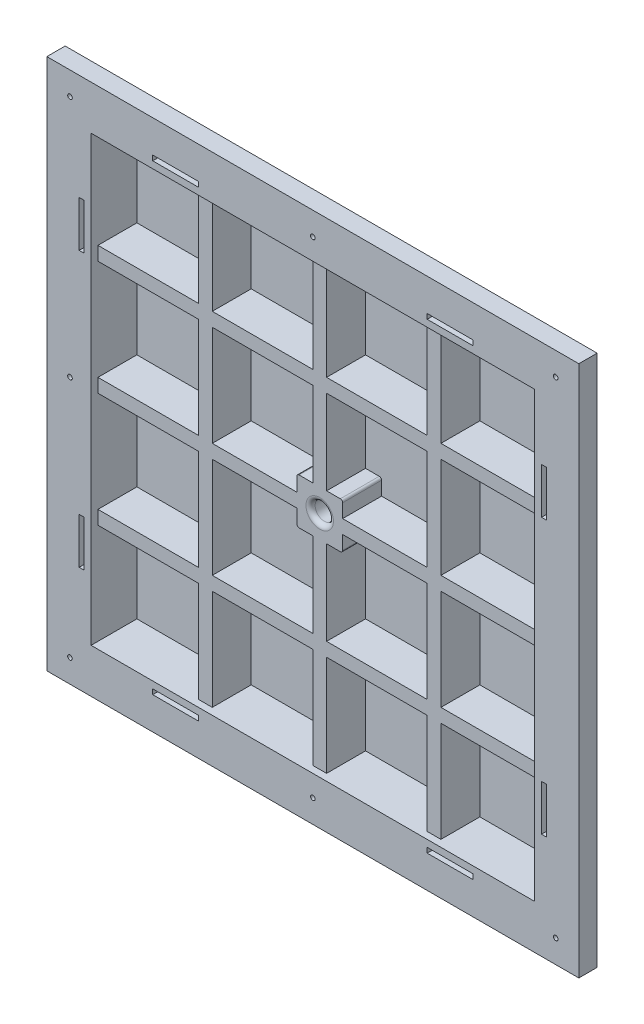
SolidWorks part; units mm, degrees
ref_plane "Front Plane" through (0, 0, 0) normal (0, 0, 1) x (1, 0, 0)
ref_plane "Top Plane" through (0, 0, 0) normal (0, 1, 0) x (1, 0, 0)
ref_plane "Right Plane" through (0, 0, 0) normal (1, 0, 0) x (0, 0, -1)
sketch "Sketch1" plane through (0, 0, 1355.7244) normal (0, 0, 1) x (1, 0, 0)
  line L22 (813.5427, 831.1782) -> (813.5427, 1030.7782)
  line L23 (613.9427, 831.1782) -> (813.5427, 831.1782)
  line L24 (613.9427, 1030.7782) -> (613.9427, 831.1782)
  line L25 (813.5427, 1030.7782) -> (613.9427, 1030.7782)
  line L26 (813.5427, 831.1782) -> (813.5427, 1030.7782)
  line L27 (613.9427, 831.1782) -> (813.5427, 831.1782)
  line L28 (613.9427, 1030.7782) -> (613.9427, 831.1782)
  line L29 (813.5427, 1030.7782) -> (613.9427, 1030.7782)
  dimension "D1" = 2.2
extrude "Boss-Extrude1" add sketch "Sketch1" against normal blind 20
sketch "Sketch2" plane through (0, 0, 1355.7244) normal (0, 0, 1) x (1, 0, 0)
  line L0 (826.8427, 1044.0782) -> (600.6427, 1044.0782)
  line L1 (600.6427, 1044.0782) -> (600.6427, 817.8782)
  line L2 (600.6427, 817.8782) -> (826.8427, 817.8782)
  line L3 (826.8427, 817.8782) -> (826.8427, 1044.0782)
  line L8 (823.8427, 820.8782) -> (823.8427, 1041.0782)
  line L9 (823.8427, 1041.0782) -> (603.6427, 1041.0782)
  line L10 (603.6427, 1041.0782) -> (603.6427, 820.8782)
  line L11 (603.6427, 820.8782) -> (823.8427, 820.8782)
  line L12 (823.8427, 820.8782) -> (823.8427, 1041.0782)
  line L13 (823.8427, 1041.0782) -> (603.6427, 1041.0782)
  line L14 (603.6427, 1041.0782) -> (603.6427, 820.8782)
  line L15 (603.6427, 820.8782) -> (823.8427, 820.8782)
  dimension "D1" = 0.1
  dimension "D2" = 3
extrude "Boss-Extrude2" add sketch "Sketch2" against normal blind 5 separate body
sketch "Sketch3" plane through (0, 0, 1355.7244) normal (0, 0, 1) x (1, 0, 0)
  line L4 (616.9427, 930.9782) -> (810.5427, 930.9782) construction
  line L5 (616.9427, 927.9782) -> (660.8427, 927.9782)
  line L6 (616.9427, 933.9782) -> (660.8427, 933.9782)
  line L7 (713.7427, 1027.7782) -> (713.7427, 834.1782) construction
  line L8 (616.9427, 834.1782) -> (810.5427, 834.1782)
  line L9 (810.5427, 834.1782) -> (810.5427, 1027.7782)
  line L10 (810.5427, 1027.7782) -> (616.9427, 1027.7782)
  line L11 (616.9427, 1027.7782) -> (616.9427, 834.1782)
  line L12 (616.9427, 834.1782) -> (660.8427, 834.1782)
  line L13 (810.5427, 834.1782) -> (810.5427, 878.0782)
  line L14 (810.5427, 1027.7782) -> (766.6427, 1027.7782)
  line L15 (616.9427, 1027.7782) -> (616.9427, 983.8782)
  line L16 (710.7427, 1027.7782) -> (710.7427, 983.8782)
  line L17 (716.7427, 1027.7782) -> (716.7427, 983.8782)
  line L18 (716.7427, 933.9782) -> (760.6427, 933.9782)
  line L19 (616.9427, 933.9782) -> (810.5427, 933.9782) construction
  line L20 (710.7427, 927.9782) -> (710.7427, 884.0782)
  line L21 (710.7427, 1027.7782) -> (710.7427, 834.1782) construction
  line L22 (716.7427, 927.9782) -> (716.7427, 884.0782)
  line L23 (716.7427, 1027.7782) -> (716.7427, 834.1782) construction
  line L24 (716.7427, 927.9782) -> (760.6427, 927.9782)
  line L25 (616.9427, 927.9782) -> (810.5427, 927.9782) construction
  line L26 (663.8427, 933.9782) -> (663.8427, 1027.7782) construction
  line L27 (710.7427, 980.8782) -> (616.9427, 980.8782) construction
  line L28 (666.8427, 933.9782) -> (666.8427, 977.8782)
  line L29 (660.8427, 933.9782) -> (660.8427, 977.8782)
  line L30 (710.7427, 983.8782) -> (666.8427, 983.8782)
  line L31 (710.7427, 977.8782) -> (666.8427, 977.8782)
  line L32 (660.8427, 983.8782) -> (616.9427, 983.8782)
  line L33 (710.7427, 983.8782) -> (616.9427, 983.8782) construction
  line L34 (660.8427, 983.8782) -> (660.8427, 1027.7782)
  line L35 (660.8427, 933.9782) -> (660.8427, 1027.7782) construction
  line L36 (666.8427, 983.8782) -> (666.8427, 1027.7782)
  line L37 (666.8427, 933.9782) -> (666.8427, 1027.7782) construction
  line L38 (660.8427, 977.8782) -> (616.9427, 977.8782)
  line L39 (710.7427, 977.8782) -> (616.9427, 977.8782) construction
  line L40 (760.6427, 933.9782) -> (760.6427, 977.8782)
  line L41 (766.6427, 933.9782) -> (766.6427, 977.8782)
  line L42 (766.6427, 977.8782) -> (810.5427, 977.8782)
  line L43 (766.6427, 983.8782) -> (810.5427, 983.8782)
  line L44 (716.7427, 983.8782) -> (760.6427, 983.8782)
  line L45 (716.7427, 977.8782) -> (760.6427, 977.8782)
  line L46 (760.6427, 983.8782) -> (760.6427, 1027.7782)
  line L47 (766.6427, 983.8782) -> (766.6427, 1027.7782)
  line L48 (710.7427, 881.0782) -> (616.9427, 881.0782) construction
  line L49 (663.8427, 927.9782) -> (663.8427, 834.1782) construction
  line L50 (766.6427, 878.0782) -> (766.6427, 834.1782)
  line L51 (760.6427, 878.0782) -> (760.6427, 834.1782)
  line L52 (716.7427, 884.0782) -> (760.6427, 884.0782)
  line L53 (716.7427, 878.0782) -> (760.6427, 878.0782)
  line L54 (766.6427, 878.0782) -> (810.5427, 878.0782)
  line L55 (766.6427, 884.0782) -> (810.5427, 884.0782)
  line L56 (766.6427, 927.9782) -> (766.6427, 884.0782)
  line L57 (760.6427, 927.9782) -> (760.6427, 884.0782)
  line L58 (660.8427, 884.0782) -> (616.9427, 884.0782)
  line L59 (666.8427, 878.0782) -> (666.8427, 834.1782)
  line L60 (660.8427, 878.0782) -> (660.8427, 834.1782)
  line L61 (660.8427, 878.0782) -> (616.9427, 878.0782)
  line L62 (710.7427, 884.0782) -> (666.8427, 884.0782)
  line L63 (710.7427, 878.0782) -> (666.8427, 878.0782)
  line L64 (660.8427, 927.9782) -> (660.8427, 884.0782)
  line L65 (666.8427, 927.9782) -> (666.8427, 884.0782)
  line L66 (760.6427, 1027.7782) -> (716.7427, 1027.7782)
  line L67 (810.5427, 983.8782) -> (810.5427, 1027.7782)
  line L68 (710.7427, 1027.7782) -> (666.8427, 1027.7782)
  line L69 (660.8427, 1027.7782) -> (616.9427, 1027.7782)
  line L70 (616.9427, 977.8782) -> (616.9427, 933.9782)
  line L71 (710.7427, 977.8782) -> (710.7427, 933.9782)
  line L72 (716.7427, 977.8782) -> (716.7427, 933.9782)
  line L73 (810.5427, 933.9782) -> (810.5427, 977.8782)
  line L74 (666.8427, 933.9782) -> (710.7427, 933.9782)
  line L75 (666.8427, 927.9782) -> (710.7427, 927.9782)
  line L76 (616.9427, 927.9782) -> (616.9427, 884.0782)
  line L77 (616.9427, 878.0782) -> (616.9427, 834.1782)
  line L78 (666.8427, 834.1782) -> (710.7427, 834.1782)
  line L79 (716.7427, 834.1782) -> (760.6427, 834.1782)
  line L80 (710.7427, 878.0782) -> (710.7427, 834.1782)
  line L81 (716.7427, 878.0782) -> (716.7427, 834.1782)
  line L82 (810.5427, 884.0782) -> (810.5427, 927.9782)
  line L83 (766.6427, 834.1782) -> (810.5427, 834.1782)
  line L84 (766.6427, 927.9782) -> (810.5427, 927.9782)
  line L85 (766.6427, 933.9782) -> (810.5427, 933.9782)
  dimension "D1" = 3
  dimension "D2" = 3
  dimension "D3" = 3
  dimension "D4" = 3
  dimension "D5" = 3
  dimension "D6" = 3
  dimension "D7" = 3
  dimension "D8" = 3
  dimension "D9" = 3
extrude "Cut-Extrude2" cut sketch "Sketch3" against normal offset from surface (17 mm away) 3 up to face at (713.7427, 930.9782, 1335.7244)
sketch "Sketch4" plane through (0, 0, 1355.7244) normal (0, 0, 1) x (1, 0, 0)
  line L1 (600.6427, 1044.0782) -> (826.8427, 1044.0782)
  line L2 (600.6427, 1044.0782) -> (600.6427, 817.8782)
  line L3 (600.6427, 817.8782) -> (826.8427, 817.8782)
  line L4 (826.8427, 1044.0782) -> (826.8427, 817.8782)
  line L5 (810.5427, 834.1782) -> (616.9427, 834.1782)
  line L6 (810.5427, 834.1782) -> (810.5427, 1027.7782)
  line L7 (810.5427, 1027.7782) -> (616.9427, 1027.7782)
  line L8 (616.9427, 834.1782) -> (616.9427, 1027.7782)
  circle A0 centre (607.7427, 1036.9782) radius 1
  circle A1 centre (713.7427, 1036.9782) radius 1
  circle A2 centre (819.7427, 1036.9782) radius 1
  circle A3 centre (607.7427, 930.9782) radius 1
  circle A4 centre (607.7427, 824.9782) radius 1
  circle A5 centre (713.7427, 824.9782) radius 1
  circle A6 centre (819.7427, 824.9782) radius 1
extrude "Boss-Extrude3" add sketch "Sketch4" along normal blind 3
sketch "Sketch5" plane through (0, 0, 1355.7244) normal (0, 0, -1) x (-1, 0, 0)
  line L0 (-813.5427, 1030.7782) -> (-713.7427, 1030.7782) construction
  line L1 (-813.5427, 1030.7782) -> (-613.9427, 1030.7782) construction
  line L2 (-763.6427, 1030.7782) -> (-783.6427, 1030.7782)
  line L3 (-783.6427, 1030.7782) -> (-783.6427, 1032.9782)
  line L4 (-815.7427, 1032.9782) -> (-611.7427, 1032.9782) construction
  line L5 (-783.6427, 1032.9782) -> (-763.6427, 1032.9782)
  line L6 (-763.6427, 1032.9782) -> (-763.6427, 1030.7782)
  line L7 (-713.7427, 1030.7782) -> (-713.7427, 831.1782) construction
  line L8 (-613.9427, 831.1782) -> (-813.5427, 831.1782) construction
  line L9 (-613.9427, 930.9782) -> (-813.5427, 930.9782) construction
  line L10 (-613.9427, 1030.7782) -> (-613.9427, 831.1782) construction
  line L11 (-813.5427, 831.1782) -> (-813.5427, 1030.7782) construction
  line L12 (-763.6427, 828.9782) -> (-763.6427, 831.1782)
  line L13 (-783.6427, 828.9782) -> (-763.6427, 828.9782)
  line L14 (-783.6427, 831.1782) -> (-783.6427, 828.9782)
  line L15 (-763.6427, 831.1782) -> (-783.6427, 831.1782)
  line L16 (-663.8427, 831.1782) -> (-643.8427, 831.1782)
  line L17 (-643.8427, 831.1782) -> (-643.8427, 828.9782)
  line L18 (-643.8427, 828.9782) -> (-663.8427, 828.9782)
  line L19 (-663.8427, 828.9782) -> (-663.8427, 831.1782)
  line L20 (-663.8427, 1032.9782) -> (-663.8427, 1030.7782)
  line L21 (-643.8427, 1032.9782) -> (-663.8427, 1032.9782)
  line L22 (-643.8427, 1030.7782) -> (-643.8427, 1032.9782)
  line L23 (-663.8427, 1030.7782) -> (-643.8427, 1030.7782)
  line L24 (-813.5427, 1030.7782) -> (-613.9427, 831.1782) construction
  line L25 (-813.5427, 881.0782) -> (-813.5427, 861.0782)
  line L26 (-813.5427, 861.0782) -> (-815.7427, 861.0782)
  line L27 (-815.7427, 861.0782) -> (-815.7427, 881.0782)
  line L28 (-815.7427, 881.0782) -> (-813.5427, 881.0782)
  line L29 (-815.7427, 980.8782) -> (-813.5427, 980.8782)
  line L30 (-815.7427, 1000.8782) -> (-815.7427, 980.8782)
  line L31 (-813.5427, 1000.8782) -> (-815.7427, 1000.8782)
  line L32 (-813.5427, 980.8782) -> (-813.5427, 1000.8782)
  line L33 (-815.7427, 828.9782) -> (-611.7427, 1032.9782) construction
  line L34 (-613.9427, 980.8782) -> (-613.9427, 1000.8782)
  line L35 (-613.9427, 1000.8782) -> (-611.7427, 1000.8782)
  line L36 (-611.7427, 1000.8782) -> (-611.7427, 980.8782)
  line L37 (-611.7427, 980.8782) -> (-613.9427, 980.8782)
  line L38 (-611.7427, 881.0782) -> (-613.9427, 881.0782)
  line L39 (-611.7427, 861.0782) -> (-611.7427, 881.0782)
  line L40 (-613.9427, 861.0782) -> (-611.7427, 861.0782)
  line L41 (-613.9427, 881.0782) -> (-613.9427, 861.0782)
extrude "Cut-Extrude3" cut sketch "Sketch5" against normal through all
sketch "Sketch6" plane through (0, 0, 1358.7244) normal (0, 0, 1) x (1, 0, 0)
  line L0 (597.6427, 1047.0782) -> (597.6427, 814.8782)
  line L1 (600.6427, 1044.0782) -> (826.8427, 1044.0782)
  line L2 (600.6427, 1044.0782) -> (600.6427, 817.8782)
  line L3 (600.6427, 817.8782) -> (826.8427, 817.8782)
  line L4 (826.8427, 1044.0782) -> (826.8427, 817.8782)
  line L5 (597.6427, 814.8782) -> (829.8427, 814.8782)
  line L6 (829.8427, 1047.0782) -> (829.8427, 814.8782)
  line L7 (597.6427, 1047.0782) -> (829.8427, 1047.0782)
  dimension "D1" = 3
extrude "Boss-Extrude4" add sketch "Sketch6" against normal up to surface (8 mm away) up to face at (713.7427, 930.9782, 1350.7244)
sketch "Sketch7" plane through (0, 0, 1355.7244) normal (0, 0, 1) x (1, 0, 0)
  line L0 (710.7427, 933.9782) -> (716.7427, 927.9782) construction
  line L1 (716.7427, 933.9782) -> (710.7427, 927.9782) construction
  line L3 (703.7427, 930.9782) -> (703.7427, 940.9782)
  line L4 (703.7427, 940.9782) -> (723.7427, 940.9782)
  line L5 (723.7427, 940.9782) -> (723.7427, 920.9782)
  line L6 (723.7427, 920.9782) -> (703.7427, 920.9782)
  line L7 (703.7427, 920.9782) -> (703.7427, 930.9782)
extrude "Boss-Extrude5" add sketch "Sketch7" against normal up to surface (20 mm away) up to face at (713.7427, 930.9782, 1335.7244)
sketch "Sketch8" plane through (0, 0, 1355.7244) normal (0, 0, 1) x (1, 0, 0)
  line L0 (703.7427, 940.9782) -> (723.7427, 920.9782) construction
  line L1 (723.7427, 940.9782) -> (703.7427, 920.9782) construction
  circle A0 centre (713.7427, 930.9782) radius 4
extrude "Cut-Extrude4" cut sketch "Sketch8" against normal through all
fillet "Fillet1" radius 2 1 edges at (717.7427, 930.9782, 1355.7244)
fillet "Fillet2" radius 1 4 edges at (703.7427, 920.9782, 1347.2244) (703.7427, 940.9782, 1347.2244) (723.7427, 920.9782, 1347.2244) (723.7427, 940.9782, 1347.2244)
sketch "Sketch9" plane through (0, 0, 1350.7244) normal (0, 0, -1) x (-1, 0, 0)
  line L19 (-813.5427, 1030.7782) -> (-613.9427, 1030.7782)
  line L20 (-813.5427, 1030.7782) -> (-813.5427, 831.1782)
  line L21 (-813.5427, 831.1782) -> (-613.9427, 831.1782)
  line L22 (-603.4927, 820.7282) -> (-603.4927, 1041.2282)
  line L23 (-823.9927, 820.7282) -> (-603.4927, 820.7282)
  line L24 (-823.9927, 1041.2282) -> (-823.9927, 820.7282)
  line L25 (-603.4927, 1041.2282) -> (-823.9927, 1041.2282)
  line L26 (-603.4927, 820.7282) -> (-603.4927, 1041.2282)
  line L27 (-823.9927, 820.7282) -> (-603.4927, 820.7282)
  line L28 (-823.9927, 1041.2282) -> (-823.9927, 820.7282)
  line L29 (-603.4927, 1041.2282) -> (-823.9927, 1041.2282)
  line L30 (-613.9427, 1030.7782) -> (-613.9427, 831.1782)
  dimension "D1" = 0.15
extrude "Cut-Extrude5" cut sketch "Sketch9" against normal up to surface (5 mm away) up to face at (713.7427, 930.9782, 1355.7244)
fillet "Fillet4" radius 2 4 edges at (713.7427, 820.7282, 1350.7244) (603.4927, 930.9782, 1350.7244) (713.7427, 1041.2282, 1350.7244) (823.9927, 930.9782, 1350.7244)
